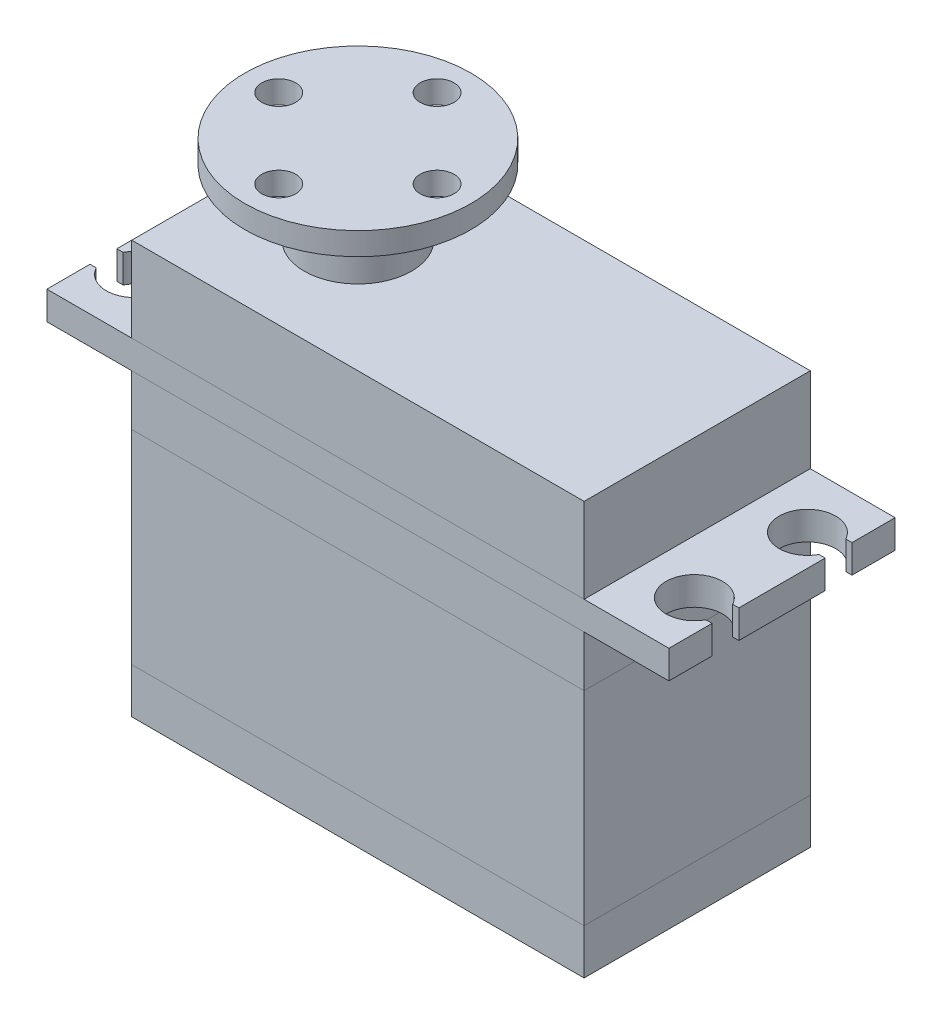
SolidWorks part; units mm, degrees
ref_plane "前视基准面" through (0, 0, 0) normal (0, 0, 1) x (1, 0, 0)
ref_plane "上视基准面" through (0, 0, 0) normal (0, 1, 0) x (1, 0, 0)
ref_plane "右视基准面" through (0, 0, 0) normal (1, 0, 0) x (0, 0, -1)
sketch "草图1" plane through (0, 0, 0) normal (0, 1, 0) x (1, 0, 0)
  line L1 (-20, 10) -> (20, 10)
  line L2 (-20, 10) -> (-20, -10)
  line L3 (-20, -10) -> (20, -10)
  line L4 (20, 10) -> (20, -10)
  line L5 (-20, 10) -> (20, -10) construction
  line L6 (-20, -10) -> (20, 10) construction
  point P0 (0, 0)
  dimension "D1" = 20
  dimension "D2" = 40
extrude "凸台-拉伸1" add sketch "草图1" along normal blind 4
sketch "草图2" plane through (0, 4, 0) normal (0, 1, 0) x (1, 0, 0)
  line L1 (-20, 10) -> (20, 10)
  line L2 (-20, 10) -> (-20, -10)
  line L3 (-20, -10) -> (20, -10)
  line L4 (20, 10) -> (20, -10)
  line L5 (-20, 10) -> (20, -10) construction
  line L6 (-20, -10) -> (20, 10) construction
  point P0 (0, 0)
extrude "凸台-拉伸2" add sketch "草图2" along normal blind 18 separate body
sketch "草图3" plane through (0, 22, 0) normal (0, 1, 0) x (1, 0, 0)
  line L0 (20, -10) -> (20, 10) construction
  line L1 (-20, 10) -> (20, 10)
  line L2 (-20, 10) -> (-20, -10)
  line L3 (-20, -10) -> (20, -10)
  line L4 (20, 10) -> (20, -10)
  line L5 (-20, 10) -> (20, -10) construction
  line L6 (-20, -10) -> (20, 10) construction
  line L7 (-20, -10) -> (20, -10) construction
  point P0 (0, 0)
extrude "凸台-拉伸3" add sketch "草图3" along normal blind 4.5 separate body
sketch "草图4" plane through (0, 26.5, 0) normal (0, 1, 0) x (1, 0, 0)
  line L1 (-27.5, 10) -> (27.5, 10)
  line L2 (-27.5, 10) -> (-27.5, -10)
  line L3 (-27.5, -10) -> (27.5, -10)
  line L4 (27.5, 10) -> (27.5, -10)
  line L5 (-27.5, 10) -> (27.5, -10) construction
  line L6 (-27.5, -10) -> (27.5, 10) construction
  point P0 (0, 0)
  dimension "D1" = 20
  dimension "D2" = 55
extrude "凸台-拉伸4" add sketch "草图4" along normal blind 2.5 separate body
sketch "草图5" plane through (0, 29, 0) normal (0, 1, 0) x (1, 0, 0)
  line L1 (-20, 10) -> (20, 10)
  line L2 (-20, 10) -> (-20, -10)
  line L3 (-20, -10) -> (20, -10)
  line L4 (20, 10) -> (20, -10)
  line L5 (-20, 10) -> (20, -10) construction
  line L6 (-20, -10) -> (20, 10) construction
  line L7 (-27.5, -10) -> (27.5, -10) construction
  point P0 (0, 0)
  dimension "D1" = 20
  dimension "D2" = 40
extrude "凸台-拉伸5" add sketch "草图5" along normal blind 7.5 separate body
sketch "草图6" plane through (0, 36.5, 0) normal (0, 1, 0) x (1, 0, 0)
  line L0 (-31.0678, 0) -> (40.9885, 0) construction
  line L1 (24.75, -5) -> (-24.75, -5) construction
  line L2 (24.75, -5) -> (24.75, 5) construction
  line L3 (24.75, 5) -> (-24.75, 5) construction
  line L4 (-24.75, -5) -> (-24.75, 5) construction
  line L5 (24.75, -5) -> (-24.75, 5) construction
  line L6 (24.75, 5) -> (-24.75, -5) construction
  line L7 (-28.0648, 6.185) -> (-24.0648, 6.185)
  line L8 (-28.0648, 6.185) -> (-28.0648, 3.815)
  line L9 (-28.0648, 3.815) -> (-24.0648, 3.815)
  line L10 (-24.0648, 6.185) -> (-24.0648, 3.815)
  line L11 (-28.0648, 6.185) -> (-24.0648, 3.815) construction
  line L12 (-28.0648, 3.815) -> (-24.0648, 6.185) construction
  line L13 (0, 18.9271) -> (0, -17.8027) construction
  line L14 (28.0648, 3.815) -> (24.0648, 3.815)
  line L15 (24.0648, 6.185) -> (24.0648, 3.815)
  line L16 (28.0648, 6.185) -> (24.0648, 6.185)
  line L17 (28.0648, 6.185) -> (28.0648, 3.815)
  line L18 (28.0648, -6.185) -> (28.0648, -3.815)
  line L19 (28.0648, -6.185) -> (24.0648, -6.185)
  line L20 (24.0648, -6.185) -> (24.0648, -3.815)
  line L21 (28.0648, -3.815) -> (24.0648, -3.815)
  line L22 (-28.0648, -3.815) -> (-24.0648, -3.815)
  line L23 (-24.0648, -6.185) -> (-24.0648, -3.815)
  line L24 (-28.0648, -6.185) -> (-24.0648, -6.185)
  line L25 (-28.0648, -6.185) -> (-28.0648, -3.815)
  circle A0 centre (-24.75, 5) radius 2.5
  circle A1 centre (-24.75, -5) radius 2.5
  circle A2 centre (24.75, -5) radius 2.5
  circle A3 centre (24.75, 5) radius 2.5
  point P0 (0, 0)
  point P10 (-26.0648, 5)
  dimension "D3" = 5
  dimension "D4" = 5
  dimension "D5" = 5
  dimension "D6" = 5
  dimension "D7" = 2.37
  dimension "D1" = 10
  dimension "D2" = 49.5
  dimension "D8" = 4
extrude "切除-拉伸2" cut sketch "草图6" against normal through all contours L9 A0 L7 L10 | L7 A0 L9 L10 | A0 L7 L8 L9 | L24 A1 L22 L23 | L22 A1 L24 L23 | A1 L22 L25 L24 | L14 A3 L16 L15 | L16 A3 L14 L15 | A3 L14 L17 L16 | L21 A2 L19 L20 | L19 A2 L21 L20 | A2 L19 L18 L21
sketch "草图7" plane through (0, 36.5, 0) normal (0, 1, 0) x (1, 0, 0)
  line L0 (20, -10) -> (20, 10) construction
  circle A0 centre (-10, 0) radius 4.75
  dimension "D1" = 9.5
  dimension "D2" = 30
extrude "凸台-拉伸6" add sketch "草图7" along normal blind 5.8
sketch "草图9" plane through (0, 42.3, 0) normal (0, 1, 0) x (1, 0, 0)
  circle A0 centre (-10, 0) radius 10
  dimension "D1" = 20
extrude "凸台-拉伸7" add sketch "草图9" along normal blind 2
sketch "草图10" plane through (0, 44.3, 0) normal (0, 1, 0) x (1, 0, 0)
  circle A0 centre (-10, 0) radius 2.75
  dimension "D1" = 5.5
extrude "凸台-拉伸8" add sketch "草图10" along normal blind 2.5
sketch "草图11" plane through (0, 44.3, 0) normal (0, 1, 0) x (1, 0, 0)
  circle A0 centre (-10, 0) radius 7 construction
  circle A1 centre (-10, 7) radius 1.5
  circle A2 centre (-17, 0) radius 1.5
  circle A3 centre (-10, -7) radius 1.5
  circle A4 centre (-3, 0) radius 1.5
  dimension "D1" = 14
  dimension "D2" = 3
  dimension "D3" = 3
  dimension "D4" = 3
  dimension "D5" = 3
extrude "切除-拉伸3" cut sketch "草图11" against normal blind 2.8
cosmetic thread "装饰螺纹线1" parameters "D2"=4
cosmetic thread "装饰螺纹线2" parameters "D2"=4
cosmetic thread "装饰螺纹线3" parameters "D2"=4
cosmetic thread "装饰螺纹线4" parameters "D2"=4
sketch "草图12" plane through (0, 46.8, 0) normal (0, 1, 0) x (1, 0, 0)
  line L1 (-9.2516, -1.2342) -> (-8.557, 0.031)
  line L2 (-8.557, 0.031) -> (-9.3054, 1.2652)
  line L3 (-9.3054, 1.2652) -> (-10.7484, 1.2342)
  line L4 (-10.7484, 1.2342) -> (-11.443, -0.031)
  line L5 (-11.443, -0.031) -> (-10.6946, -1.2652)
  line L6 (-10.6946, -1.2652) -> (-9.2516, -1.2342)
  circle A0 centre (-10, 0) radius 1.25 construction
  dimension "D1" = 2.5
extrude "切除-拉伸4" cut sketch "草图12" against normal blind 1
sketch "草图13" plane through (0, 46.8, 0) normal (0, 1, 0) x (1, 0, 0)
  circle A0 centre (-10, 0) radius 2.75
extrude "切除-拉伸5" cut sketch "草图13" against normal blind 2.5
